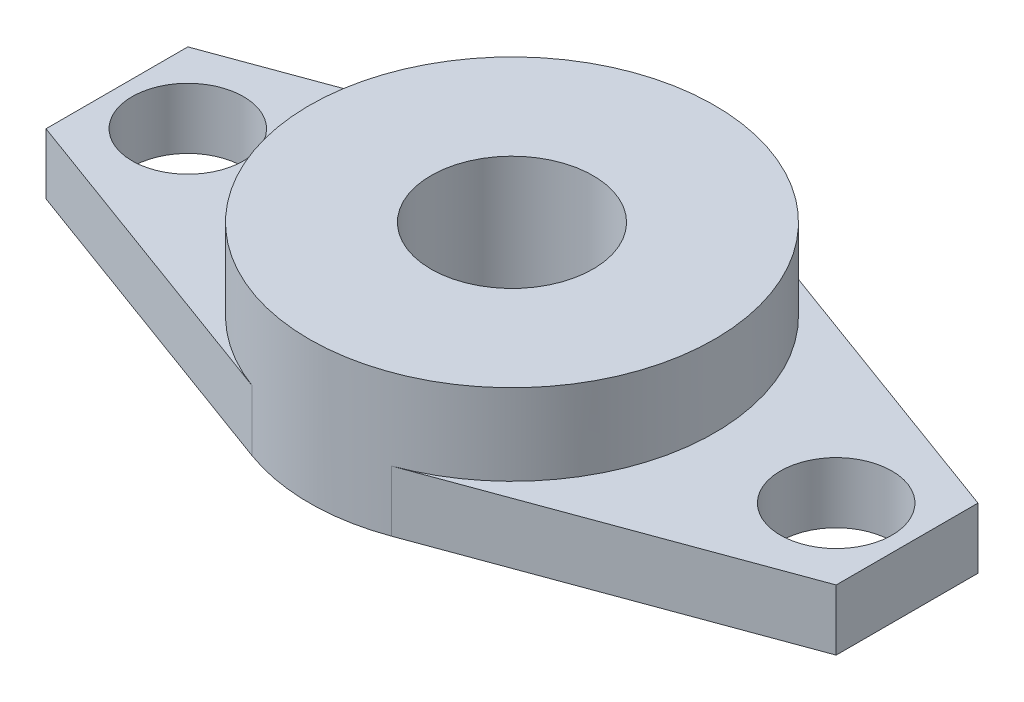
SolidWorks part; units mm, degrees
material "201.0-T43 绝缘成型铸件 (SS)"
ref_plane "前视基准面" through (0, 0, 0) normal (0, 0, 1) x (1, 0, 0)
ref_plane "上视基准面" through (0, 0, 0) normal (0, 1, 0) x (1, 0, 0)
ref_plane "右视基准面" through (0, 0, 0) normal (1, 0, 0) x (0, 0, -1)
sketch "草图1" plane through (0, 0, 0) normal (0, 1, 0) x (1, 0, 0)
  line L0 (-280.0372, 0) -> (13721.8235, 0) construction
  line L1 (0, -280.0372) -> (0, 13721.8235) construction
  line L2 (-19.5, 3.5) -> (-19.5, -3.5)
  line L3 (-19.5, 3.5) -> (-3.4431, 9.3886)
  line L4 (-19.5, -3.5) -> (-3.4431, -9.3886)
  line L5 (19.5, -3.5) -> (3.4431, -9.3886)
  line L6 (19.5, 3.5) -> (3.4431, 9.3886)
  line L7 (19.5, 3.5) -> (19.5, -3.5)
  circle A0 centre (-16, 0) radius 2.75
  circle A1 centre (0, 0) radius 10 construction
  arc A2 (-3.4431, 9.3886) -> (3.4431, 9.3886) centre (0, 0) cw
  arc A3 (-3.4431, -9.3886) -> (3.4431, -9.3886) centre (0, 0) ccw
  circle A4 centre (0, 0) radius 4
  circle A5 centre (16, 0) radius 2.75
  point P8 (-19.5, 0)
  point P21 (19.5, 0)
  dimension "D3" = 5.5
  dimension "D5" = 20
  dimension "D6" = 8
  dimension "D1" = 7
  dimension "D2" = 19.5
  dimension "D4" = 16
extrude "凸台-拉伸1" add sketch "草图1" along normal blind 3
sketch "草图2" plane through (0, 3, 0) normal (0, 1, 0) x (1, 0, 0)
  circle A0 centre (0, 0) radius 10 construction
  circle A1 centre (0, 0) radius 10
  circle A2 centre (0, 0) radius 4 construction
  circle A3 centre (0, 0) radius 4
extrude "凸台-拉伸2" add sketch "草图2" along normal blind 4
